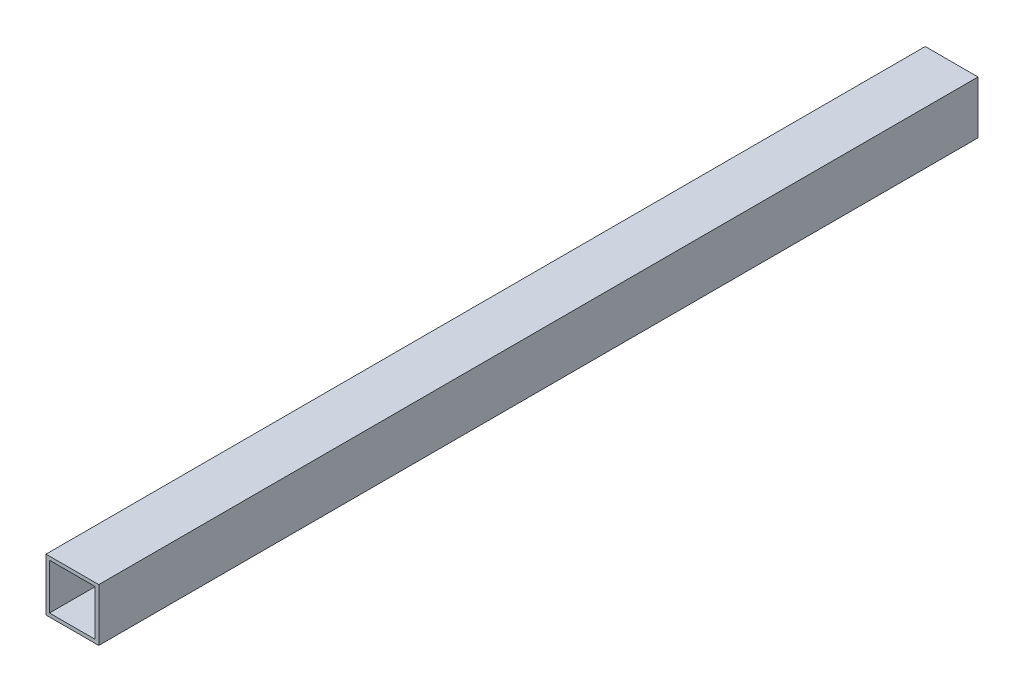
SolidWorks part; units mm, degrees
ref_plane "Front Plane" through (0, 0, 0) normal (0, 0, 1) x (1, 0, 0)
ref_plane "Top Plane" through (0, 0, 0) normal (0, 1, 0) x (1, 0, 0)
ref_plane "Right Plane" through (0, 0, 0) normal (1, 0, 0) x (0, 0, -1)
sketch "Esboço2" plane through (0, 0, 0) normal (0, 0, 1) x (1, 0, 0)
  line L1 (-94.2052, 59.6622) -> (-64.2052, 59.6622)
  line L2 (-94.2052, 59.6622) -> (-94.2052, 29.6622)
  line L3 (-94.2052, 29.6622) -> (-64.2052, 29.6622)
  line L4 (-64.2052, 59.6622) -> (-64.2052, 29.6622)
  dimension "D1" = 30
  dimension "D2" = 30
extrude "Ressalto-extrusão1" add sketch "Esboço2" along normal blind 500
shell "Casca2" thickness 2
